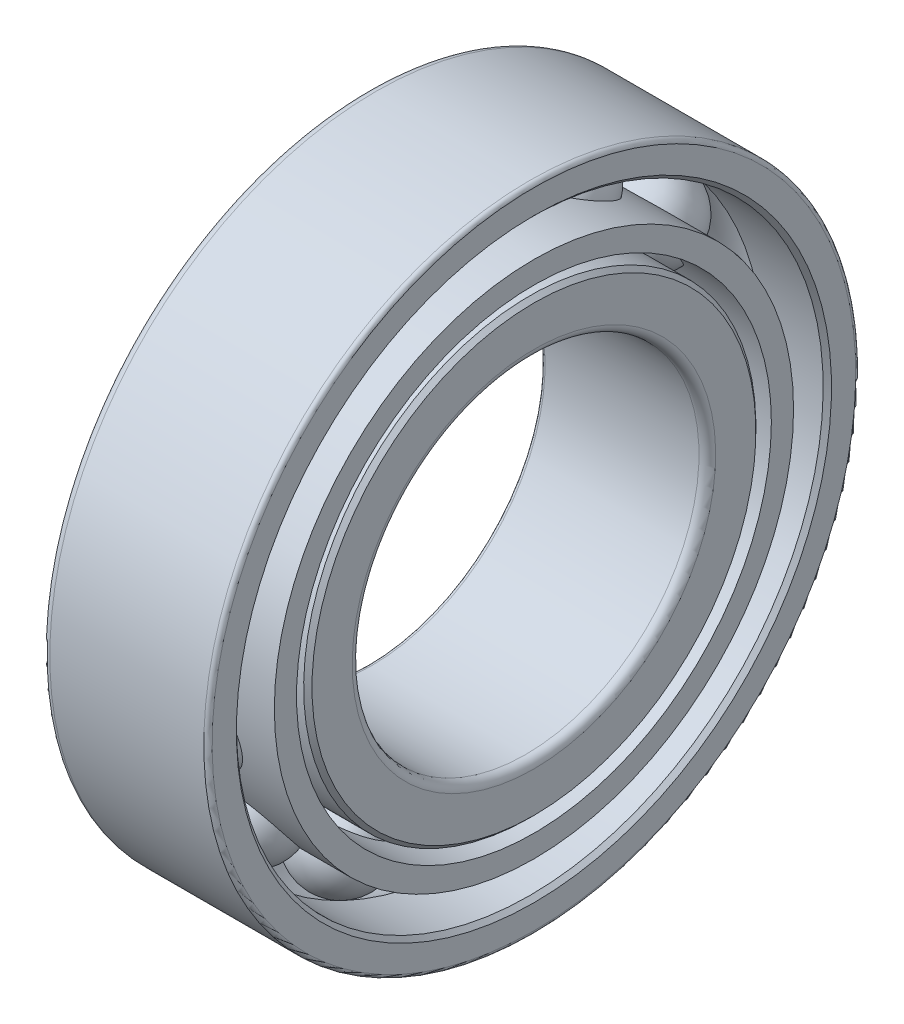
SolidWorks part; units mm, degrees
ref_plane "Front Plane" through (0, 0, 0) normal (0, 0, 1) x (1, 0, 0)
ref_plane "Top Plane" through (0, 0, 0) normal (0, 1, 0) x (1, 0, 0)
ref_plane "Right Plane" through (0, 0, 0) normal (1, 0, 0) x (0, 0, -1)
sketch "Sketch1" plane through (0, 0, 0) normal (1, 0, 0) x (0, 0, -1)
  line L0 (0, -23.5) -> (0, 23.5) construction
  circle A0 centre (0, 0) radius 23.5 construction
  circle A1 centre (0, 0) radius 21.45 construction
  circle A2 centre (0, 0) radius 12.5 construction
  circle A3 centre (0, 0) radius 19.7 construction
  circle A4 centre (0, 0) radius 16.3 construction
  circle A5 centre (0, 0) radius 15.45 construction
  circle A6 centre (0, 0) radius 0.6 construction
  circle A7 centre (0, 0) radius 0.3 construction
  point P9 (0, 0)
  point P11 (0, 21.45)
  point P15 (9.3068, 19.3258)
  point P16 (16.7703, 13.3739)
  point P17 (20.9122, 4.7731)
  point P18 (20.9122, -4.7731)
  point P19 (16.7703, -13.3739)
  point P20 (9.3068, -19.3258)
  point P21 (0, -21.45)
  point P22 (-9.3068, -19.3258)
  point P23 (-16.7703, -13.3739)
  point P24 (0, 0)
  point P29 (-20.9122, -4.7731)
  point P30 (-20.9122, 4.7731)
  point P31 (-16.7703, 13.3739)
  point P32 (-9.3068, 19.3258)
  dimension "ID" = 25
  dimension "OD" = 47
  dimension "D2 (Outer Shell)" = 42.9
  dimension "D1 (Outer Shell)" = 39.4
  dimension "d1 (Inner Shell)" = 32.6
  dimension "d2 (Inner Shell)" = 30.9
  dimension "r" = 0.6
  dimension "r1" = 0.3
  dimension "Ball Bearing Count" = 14
sketch "Sketch2" plane through (0, 0, 0) normal (0, 0, 1) x (1, 0, 0)
  line L0 (-6, 0) -> (6, 0) construction
  line L1 (-6, -23.5) -> (6, -23.5) construction
  line L2 (6, 23.5) -> (-6, 23.5) construction
  line L3 (-6, -23.5) -> (-6, 23.5) construction
  line L4 (4.9, 0) -> (-1.3968, 23.5) construction
  line L5 (0, -23.5) -> (0, 23.5) construction
  line L6 (0, -23.5) -> (0, 23.5) construction
  line L7 (0, -21.45) -> (0, 21.45) construction
  line L9 (0, -19.7) -> (0, 19.7) construction
  circle A0 centre (0, 18.287) radius 3.163 construction
  point P3 (0, 0)
  point P7 (0, -23.5)
  point P14 (0, 18.287)
  point P15 (0, 21.45)
  point P16 (0, 23.5)
  point P20 (0, 19.7)
  point P24 (0, 16.3)
  point P28 (0, 15.45)
  point P29 (0, 12.5)
  point P35 (0, 23.5)
  dimension "Width" = 12
  dimension "Contact Angle" = 15
  dimension "a (Load Center)" = 10.9
sketch "Sketch3" plane through (0, 0, 0) normal (0, 0, 1) x (1, 0, 0)
  line L0 (0, -23.5) -> (0, 23.5) construction
  line L1 (0, -23.5) -> (0, 23.5) construction
  line L2 (5.7, 23.5) -> (-5.4, 23.5)
  line L3 (-6, 22.9) -> (-6, 19.7)
  line L4 (-6, -23.5) -> (-6, 23.5) construction
  line L5 (-6, 19.7) -> (-2.8298, 19.7)
  line L6 (6, 21.15) -> (6, 23.2)
  line L7 (6, 21.45) -> (0, 21.45) construction
  line L8 (6, 0) -> (6, 16.3) construction
  line L9 (5.4, 12.5) -> (-5.7, 12.5)
  line L13 (-6, 15.45) -> (-1.3984, 15.45)
  line L16 (6, 13.1) -> (6, 16.3)
  line L17 (-6, 12.8) -> (-6, 15.45)
  line L18 (2.4609, 16.3) -> (6, 16.3)
  line L19 (6, 0) -> (6, 21.45) construction
  line L20 (6, 21.15) -> (1.3445, 21.15)
  circle A2 centre (0, 18.287) radius 3.163 construction
  arc A3 (-2.8298, 19.7) -> (0, 21.45) centre (0, 18.287) cw
  arc A4 (-1.3984, 15.45) -> (2.4609, 16.3) centre (0, 18.287) ccw
  arc A5 (5.4, 12.5) -> (6, 13.1) centre (5.4, 13.1) ccw
  arc A6 (-5.4, 23.5) -> (-6, 22.9) centre (-5.4, 22.9) ccw
  arc A7 (5.7, 23.5) -> (6, 23.2) centre (5.7, 23.2) cw
  arc A8 (-5.7, 12.5) -> (-6, 12.8) centre (-5.7, 12.8) cw
  arc A9 (0, 21.45) -> (1.3445, 21.15) centre (0, 18.287) cw
  point P6 (0, 23.5)
  point P18 (0, 12.5)
  point P31 (-6, 23.5)
  point P40 (-6, 12.5)
  dimension "D1" = 0.6
  dimension "D2" = 0.3
  dimension "D3" = 0.3
revolve "Revolve1" add sketch "Sketch3" angle 360 about L0
sketch "Sketch5" plane through (0, 0, 0) normal (0, 0, 1) x (1, 0, 0)
  line L0 (0, 21.45) -> (0, 15.1241)
  arc A0 (0, 15.1241) -> (0, 21.45) centre (0, 18.287) ccw
  circle A1 centre (0, 18.287) radius 3.163 construction
revolve "Revolve2" add sketch "Sketch5" angle 360 about L0
pattern_circular "CirPattern1" count 14 over 360 about axis through (0, 0, 0) along (1, 0, 0) of bodies 106
sketch "Sketch6" plane through (0, 0, 0) normal (1, 0, 0) x (0, 0, -1)
  circle A2 centre (0, 0) radius 17.115
  circle A3 centre (0, 0) radius 18.715
  dimension "D2" = 34.23
  dimension "D1" = 37.43
extrude "Boss-Extrude1" add sketch "Sketch6" along normal up to vertex (6 mm away) and the other way up to vertex (6 mm away) separate body up to point (6, 0, 0) other way up to point (-6, 0, 0)
sketch "Sketch8" plane through (0, 0, 0) normal (0, 0, 1) x (1, 0, 0)
  line L0 (0, 15.1141) -> (0, 21.46)
  line L2 (0, 15.1241) -> (0, 21.45) construction
  line L3 (-0.01, 15.1141) -> (-0.01, 21.46) construction
  circle A0 centre (0, 18.287) radius 3.163 construction
  arc A1 (0, 15.1241) -> (0, 21.45) centre (0, 18.287) ccw construction
  arc A2 (0, 15.1141) -> (0, 21.46) centre (0, 18.287) ccw
  arc A3 (-0.01, 15.1141) -> (-0.01, 21.46) centre (0, 18.287) ccw construction
  dimension "D1" = 0.01
revolve "Cut-Revolve1" cut sketch "Sketch8" angle 360 about L0
pattern_circular "CirPattern2" count 14 over 360 about axis through (0, 0, 0) along (1, 0, 0) of "Cut-Revolve1"
chamfer "Chamfer1" distance 0.3 angle 45 2 edges at (6, -21.15, 0) (-6, -19.7, 0)
chamfer "Chamfer2" distance 0.3 angle 45 2 edges at (-6, -15.45, 0) (6, -16.3, 0)
sketch "Sketch9" plane through (0, 0, 0) normal (0, 0, 1) x (1, 0, 0)
  line L1 (0, 18.287) -> (4.9, 0)
  line L2 (4.9, 0) -> (-6, 0)
  line L3 (4.9, 0) -> (-1.3968, 23.5) construction
  line L4 (-6, 15.45) -> (-1.3984, 15.45) construction
  line L5 (2.4609, 16.3) -> (6, 16.3) construction
  line L6 (6, 21.15) -> (1.3445, 21.15) construction
  line L7 (-6, 19.7) -> (-2.8298, 19.7) construction
  line L8 (-6, 15.45) -> (-1.3984, 15.45)
  line L9 (2.4609, 16.3) -> (6, 16.3)
  line L10 (6, 21.15) -> (1.3445, 21.15)
  line L11 (-6, 19.7) -> (-2.8298, 19.7)
  circle A0 centre (0, 18.287) radius 3.163 construction
  circle A1 centre (0, 18.287) radius 3.163
  point P2 (0, 18.287)
equation "\"D1@CirPattern1\"=\"Ball Bearing Count@Sketch1\""
equation "\"D1@Sketch3\"=\"r@Sketch1\""
equation "\"D2@Sketch3\"=\"r1@Sketch1\""
equation "\"D2@Sketch6\"=\"d1 (Inner Shell)@Sketch1\"*1.050"
equation "\"D1@Sketch6\"=\"D1 (Outer Shell)@Sketch1\"*.950"
equation "\"D1@CirPattern2\"=\"Ball Bearing Count@Sketch1\""
equation "\"D3@Sketch3\"=\"r1@Sketch1\""
equation "\"D1@Chamfer1\"=\"r1@Sketch1\""
equation "\"D1@Chamfer2\"=\"r1@Sketch1\""
